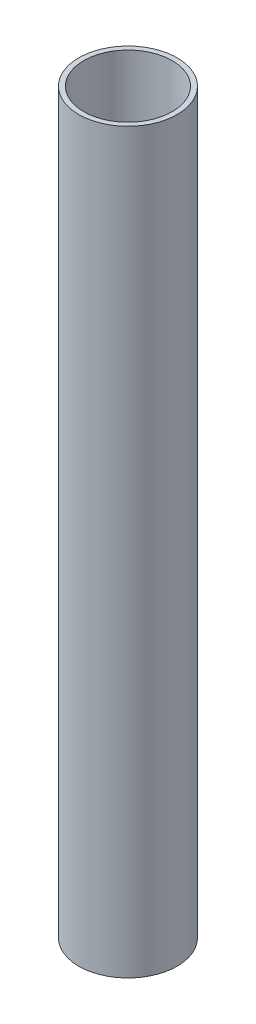
SolidWorks part; units mm, degrees
ref_plane "前视基准面" through (0, 0, 0) normal (0, 0, 1) x (1, 0, 0)
ref_plane "上视基准面" through (0, 0, 0) normal (0, 1, 0) x (1, 0, 0)
ref_plane "右视基准面" through (0, 0, 0) normal (1, 0, 0) x (0, 0, -1)
other "Configuration Table"
sketch "草图1" plane through (0, 0, 0) normal (0, 1, 0) x (1, 0, 0)
  circle A0 centre (0, 0) radius 20
  circle A1 centre (0, 0) radius 18
  dimension "D1" = 40
  dimension "D2" = 36
extrude "凸台-拉伸1" add sketch "草图1" along normal blind 300
